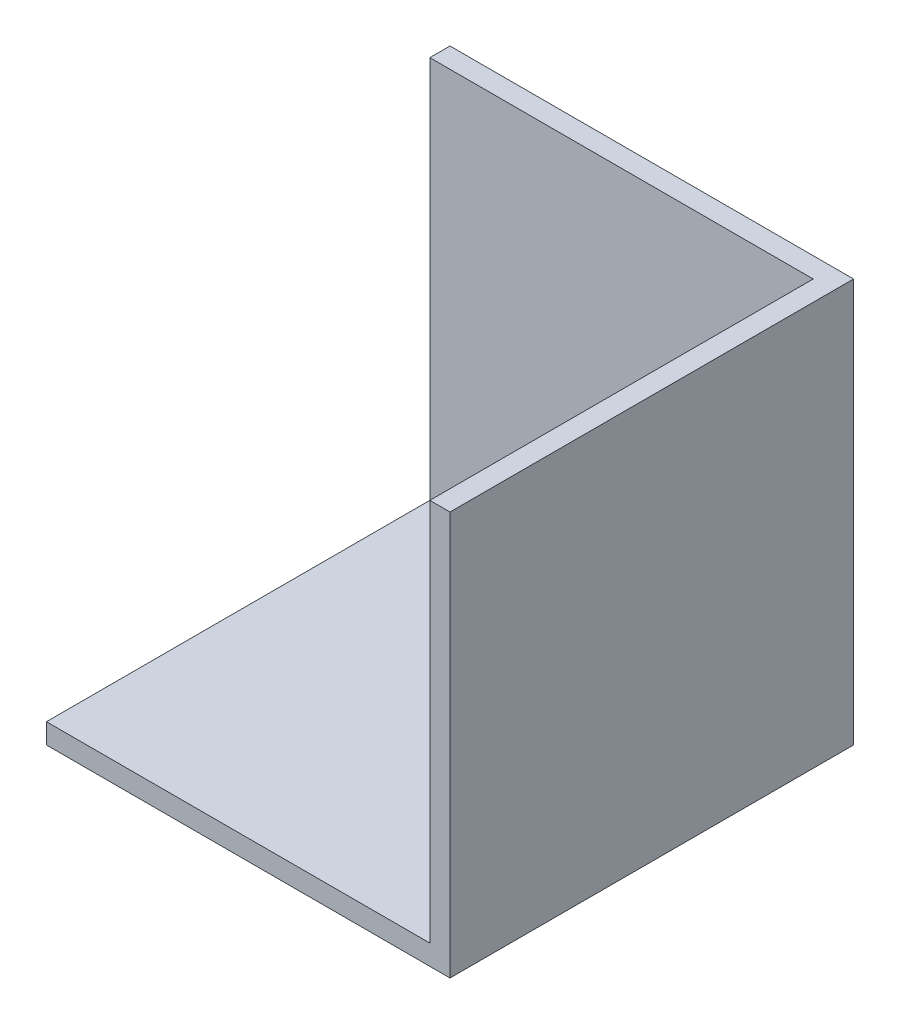
SolidWorks part; units mm, degrees
ref_plane "Front Plane" through (0, 0, 0) normal (0, 0, 1) x (1, 0, 0)
ref_plane "Top Plane" through (0, 0, 0) normal (0, 1, 0) x (1, 0, 0)
ref_plane "Right Plane" through (0, 0, 0) normal (1, 0, 0) x (0, 0, -1)
sketch "Sketch1" plane through (0, 0, 0) normal (0, 0, 1) x (1, 0, 0)
  line L1 (-50, -50) -> (50, -50)
  line L2 (-50, -50) -> (-50, 50)
  line L3 (-50, 50) -> (50, 50)
  line L4 (50, -50) -> (50, 50)
  line L5 (-50, -50) -> (50, 50) construction
  line L6 (-50, 50) -> (50, -50) construction
  point P0 (0, 0)
  dimension "D1" = 100
  dimension "D2" = 100
extrude "Boss-Extrude1" add sketch "Sketch1" along normal blind 5
sketch "Sketch4" plane through (0, 0, 5) normal (0, 0, 1) x (1, 0, 0)
  line L0 (50, 50) -> (50, -50)
  line L1 (50, -50) -> (-50, -50)
  line L2 (45, 50) -> (45, -45)
  line L3 (45, -45) -> (-50, -45)
  line L4 (45, 50) -> (50, 50)
  line L5 (-50, -45) -> (-50, -50)
  dimension "D1" = 5
extrude "Boss-Extrude4" add sketch "Sketch4" along normal blind 95
sketch "Sketch5" plane through (45, 0, 0) normal (-1, 0, 0) x (0, 0, 1)
  line L0 (0, 50) -> (100, -50) construction
  line L1 (50, 0) -> (50, 10) construction
  line L2 (0, -50) -> (100, 50) construction
  line L4 (42, 2) -> (58, 2)
  line L5 (42, 2) -> (42, 18)
  line L6 (42, 18) -> (58, 18)
  line L7 (58, 2) -> (58, 18)
  line L8 (42, 2) -> (58, 18) construction
  line L9 (42, 18) -> (58, 2) construction
  line L14 (43.5, 3.5) -> (56.5, 3.5)
  line L15 (43.5, 3.5) -> (43.5, 16.5)
  line L16 (43.5, 16.5) -> (56.5, 16.5)
  line L17 (56.5, 3.5) -> (56.5, 16.5)
  line L18 (43.5, 3.5) -> (56.5, 16.5) construction
  line L19 (43.5, 16.5) -> (56.5, 3.5) construction
  dimension "D1" = 10
  dimension "D2" = 16
  dimension "D3" = 13
  dimension "15" = 16
extrude "Boss-Extrude6" add sketch "Sketch5" along normal blind 20 contours L5 L4 L7 L6
sketch "Sketch8" plane through (25, 0, 0) normal (-1, 0, 0) x (0, 0, 1)
  line L0 (42, 2) -> (58, 18) construction
  line L1 (58, 18) -> (58, 2) construction
  line L2 (58, 2) -> (42, 18) construction
  line L3 (42, 2) -> (42, 18) construction
  line L5 (43.5, 3.5) -> (56.5, 3.5)
  line L6 (43.5, 3.5) -> (43.5, 16.5)
  line L7 (43.5, 16.5) -> (56.5, 16.5)
  line L8 (56.5, 3.5) -> (56.5, 16.5)
  line L9 (43.5, 3.5) -> (56.5, 16.5) construction
  line L10 (43.5, 16.5) -> (56.5, 3.5) construction
  point P4 (50, 10)
  dimension "D1" = 13
  dimension "D2" = 13
extrude "Cut-Extrude2" cut sketch "Sketch8" against normal blind 20
sketch "Sketch9" plane through (0, 18, 0) normal (0, 1, 0) x (1, 0, 0)
  line L0 (25, -42) -> (25, -58) construction
  line L1 (25, -49.8164) -> (45, -49.8164) construction
  line L2 (45, -42) -> (45, -58) construction
  circle A0 centre (39.3, -49.8164) radius 2
  circle A1 centre (29.3, -49.8164) radius 2
  dimension "D1" = 4
  dimension "D2" = 4
  dimension "D3" = 10
  dimension "D4" = 5.7
extrude "Cut-Extrude3" cut sketch "Sketch9" against normal blind 5
